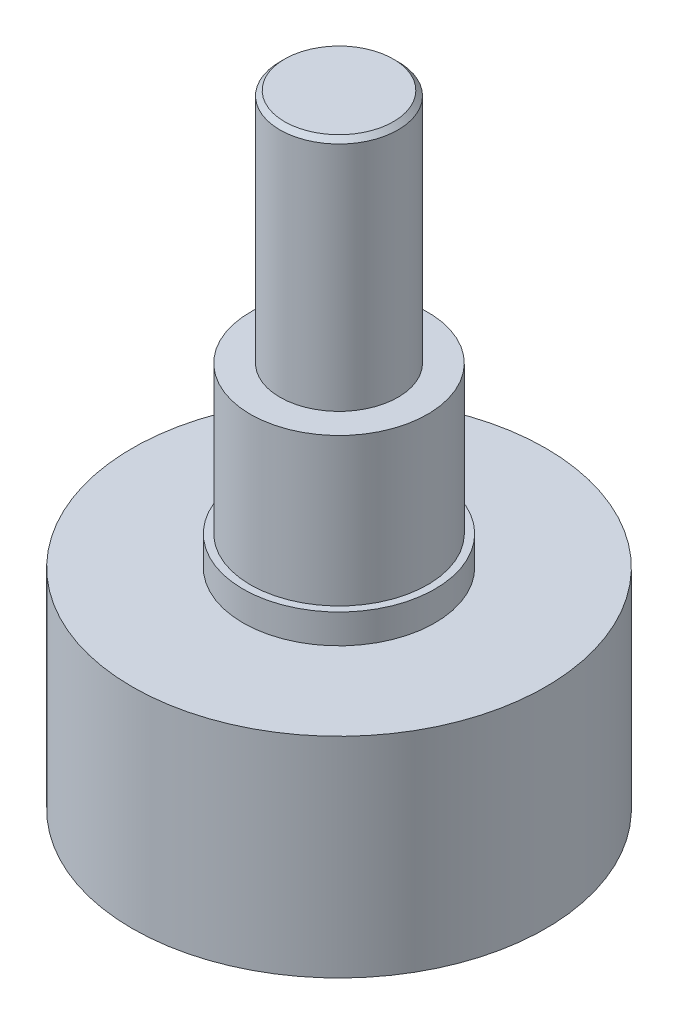
SolidWorks part; units mm, degrees
ref_plane "Front Plane" through (0, 0, 0) normal (0, 0, 1) x (1, 0, 0)
ref_plane "Top Plane" through (0, 0, 0) normal (0, 1, 0) x (1, 0, 0)
ref_plane "Right Plane" through (0, 0, 0) normal (1, 0, 0) x (0, 0, -1)
sketch "Sketch1" plane through (0, 0, 0) normal (0, 1, 0) x (1, 0, 0)
  circle A0 centre (0, 0) radius 11.1125
  dimension "D1" = 22.225
extrude "Boss-Extrude1" add sketch "Sketch1" along normal blind 11.2522
sketch "Sketch3" plane through (0, 11.2522, 0) normal (0, 1, 0) x (1, 0, 0)
  circle A0 centre (0, 0) radius 5.1587
  dimension "D1" = 10.3175
extrude "Boss-Extrude2" add sketch "Sketch3" along normal blind 1.5748
sketch "Sketch4" plane through (0, 12.827, 0) normal (0, 1, 0) x (1, 0, 0)
  circle A0 centre (0, 0) radius 4.7625
  dimension "D1" = 9.525
extrude "Boss-Extrude3" add sketch "Sketch4" along normal blind 7.9375
sketch "Sketch5" plane through (0, 20.7645, 0) normal (0, 1, 0) x (1, 0, 0)
  circle A0 centre (0, 0) radius 3.175
  dimension "D1" = 6.35
extrude "Boss-Extrude4" add sketch "Sketch5" along normal blind 12.7
chamfer "Chamfer1" distance 0.254 angle 45 1 edges at (0, 33.4645, 3.175)
